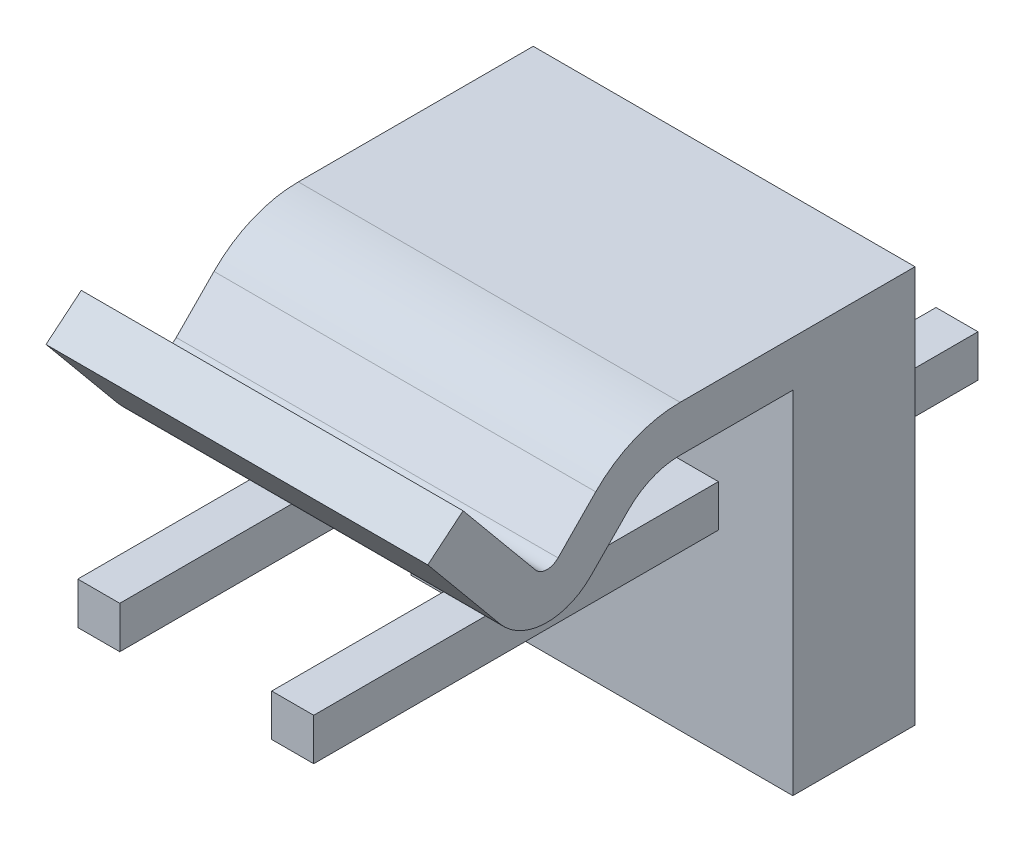
SolidWorks part; units mm, degrees
ref_plane "Front" through (0, 0, 0) normal (0, 0, 1) x (1, 0, 0)
ref_plane "Top" through (0, 0, 0) normal (0, 1, 0) x (1, 0, 0)
ref_plane "Right" through (0, 0, 0) normal (1, 0, 0) x (0, 0, -1)
sketch "Эскиз1" plane through (0, 0, 0) normal (0, 0, 1) x (1, 0, 0)
  line L1 (-1.4, -1.4) -> (1.4, -1.4)
  line L2 (-1.4, -1.4) -> (-1.4, 1.4)
  line L3 (-1.4, 1.4) -> (1.4, 1.4)
  line L4 (1.4, -1.4) -> (1.4, 1.4)
  line L5 (8.76, -1.4) -> (11.56, -1.4)
  line L6 (8.76, -1.4) -> (8.76, 1.4)
  line L7 (8.76, 1.4) -> (11.56, 1.4)
  line L8 (11.56, -1.4) -> (11.56, 1.4)
  line L9 (3.68, -1.4) -> (6.48, -1.4)
  line L10 (3.68, -1.4) -> (3.68, 1.4)
  line L11 (3.68, 1.4) -> (6.48, 1.4)
  line L12 (6.48, -1.4) -> (6.48, 1.4)
sketch "Эскиз2" plane through (0, 0, 0) normal (0, 0, 1) x (1, 0, 0)
  line L0 (-2.42, 4.8) -> (-2.42, -5.6)
  line L1 (12.58, -5.6) -> (12.58, 4.8)
  line L2 (-2.42, -5.6) -> (12.58, -5.6)
  line L4 (12.58, 4.8) -> (-2.42, 4.8)
  dimension "D1" = 2.42
  dimension "D2" = 4.8
  dimension "D3" = 15
  dimension "D4" = 5.6
extrude "Вытянуть1" add sketch "Эскиз2" along normal blind 3.2
sketch "Эскиз3" plane through (0, 0, 0) normal (0, 0, 1) x (1, 0, 0)
  line L0 (0, 0) -> (0, -0.55) construction
  line L1 (-0.55, 0.55) -> (0.55, 0.55)
  line L2 (-0.55, 0.55) -> (-0.55, -0.55)
  line L3 (-0.55, -0.55) -> (0.55, -0.55)
  line L4 (0.55, 0.55) -> (0.55, -0.55)
  line L5 (0, -0.55) -> (0, 0) construction
  line L6 (0, 0) -> (-0.55, 0) construction
  line L7 (4.53, 0.55) -> (5.63, 0.55)
  line L8 (4.53, 0.55) -> (4.53, -0.55)
  line L9 (4.53, -0.55) -> (5.63, -0.55)
  line L10 (5.63, 0.55) -> (5.63, -0.55)
  line L11 (9.61, 0.55) -> (10.71, 0.55)
  line L12 (9.61, 0.55) -> (9.61, -0.55)
  line L13 (9.61, -0.55) -> (10.71, -0.55)
  line L14 (10.71, 0.55) -> (10.71, -0.55)
  dimension "D1" = 1.1
  dimension "D2" = 1.1
  dimension "D3" = 5.08
extrude "Вытянуть2" add sketch "Эскиз3" along normal blind 13.8 and the other way blind 3.6
sketch "Эскиз4" plane through (-2.42, 0, 0) normal (-1, 0, 0) x (0, 0, 1)
  line L0 (3.2, 4.2) -> (6.1526, 4.2)
  line L1 (3.2, 4.8) -> (3.2, -5.6) construction
  line L2 (7.9346, 3.4534) -> (8.9232, 2.4487)
  line L3 (10.4063, 2.5123) -> (12.3, 4.8)
  line L4 (0, 4.8) -> (0, -5.6) construction
  line L5 (3.2, 4.8) -> (0, 4.8) construction
  line L7 (3.2, 0.55) -> (13.8, 0.55) construction
  arc A0 (6.1526, 4.2) -> (7.9346, 3.4534) centre (6.1526, 1.7) cw
  arc A1 (8.9232, 2.4487) -> (10.4063, 2.5123) centre (9.636, 3.15) ccw
  point P15 (7.2, 4.2)
  point P17 (9.7, 1.6591)
  dimension "D6" = 2.5
  dimension "D7" = 1
  dimension "D4" = 1.6
  dimension "D1" = 12.3
  dimension "D2" = 0.6
  dimension "D3" = 6.5
  dimension "D5" = 4
sketch "Эскиз5" plane through (0, 0, 3.2) normal (0, 0, 1) x (1, 0, 0)
  line L0 (12.58, -5.6) -> (12.58, 4.8) construction
  line L1 (-2.42, 4.8) -> (12.58, 4.8)
  line L2 (-2.42, 4.8) -> (-2.42, 3.6)
  line L3 (-2.42, 3.6) -> (12.58, 3.6)
  line L4 (12.58, 4.8) -> (12.58, 3.6)
  dimension "D1" = 1.2
sweep "По траектории1" add profiles "Эскиз5" path "Эскиз4"
sketch "Эскиз6" plane through (12.58, 0, 0) normal (1, 0, 0) x (0, 0, -1)
  line L1 (-15.5608, -6.9266) -> (4.3211, -6.9266)
  line L2 (-15.5608, -6.9266) -> (-15.5608, 6.5092)
  line L3 (-15.5608, 6.5092) -> (4.3211, 6.5092)
  line L4 (4.3211, -6.9266) -> (4.3211, 6.5092)
extrude "Вырез-Вытянуть1" cut sketch "Эскиз6" against normal blind 5
sketch "Эскиз7" plane through (0, 0, -3.6) normal (0, 0, -1) x (-1, 0, 0)
  circle A0 centre (0, 0) radius 0.25
  dimension "D1" = 0.5
extrude "Вырез-Вытянуть2" cut sketch "Эскиз7" against normal blind 1
